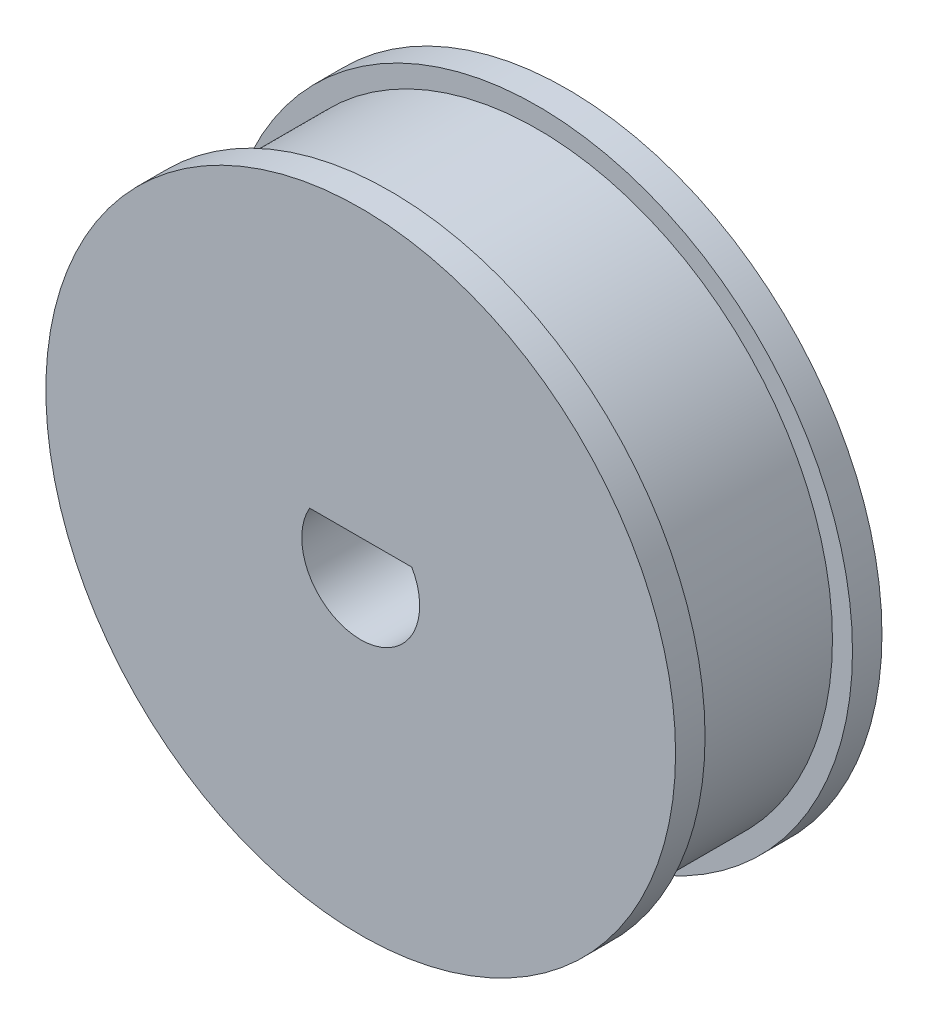
SolidWorks part; units mm, degrees
ref_plane "Front Plane" through (0, 0, 0) normal (0, 0, 1) x (1, 0, 0)
ref_plane "Top Plane" through (0, 0, 0) normal (0, 1, 0) x (1, 0, 0)
ref_plane "Right Plane" through (0, 0, 0) normal (1, 0, 0) x (0, 0, -1)
sketch "Sketch1" plane through (0, 0, 0) normal (0, 0, 1) x (1, 0, 0)
  line L0 (-1.7321, 1) -> (1.7321, 1)
  circle A0 centre (0, 0) radius 10.6792
  arc A1 (-1.7321, 1) -> (1.7321, 1) centre (0, 0) ccw
  dimension "D1" = 1
  dimension "D2" = 2
extrude "Boss-Extrude1" add sketch "Sketch1" along normal blind 7
ref_plane "Plane1" through (0, 0, 6) normal (0, 0, 1) x (1, 0, 0)
sketch "Sketch2" plane through (0, 0, 6) normal (0, 0, 1) x (1, 0, 0)
  circle A0 centre (0, 0) radius 10.6792 construction
  circle A1 centre (0, 0) radius 10.6792
  circle A2 centre (0, 0) radius 10
extrude "Cut-Extrude1" cut sketch "Sketch2" against normal blind 5
